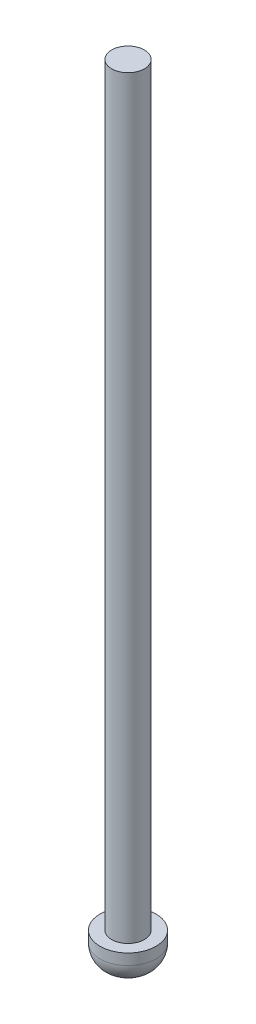
SolidWorks part; units mm, degrees
ref_plane "Alzado" through (0, 0, 0) normal (0, 0, 1) x (1, 0, 0)
ref_plane "Planta" through (0, 0, 0) normal (0, 1, 0) x (1, 0, 0)
ref_plane "Vista lateral" through (0, 0, 0) normal (1, 0, 0) x (0, 0, -1)
sketch "Croquis2" plane through (0, 0, 0) normal (0, 1, 0) x (1, 0, 0)
  circle A0 centre (0, 0) radius 17.25
  dimension "D1" = 34.5
extrude "Saliente-Extruir1" add sketch "Croquis2" along normal blind 794.82
sketch "Croquis4" plane through (0, 0, 0) normal (0, -1, 0) x (1, 0, 0)
  circle A0 centre (0, 0) radius 29.5
  dimension "D1" = 59
extrude "Saliente-Extruir2" add sketch "Croquis4" along normal blind 33.5
sketch3d "Croquis3D2"
  line L0 (0, -33.5, 0) -> (0, 0, 0) construction
  circle A0 centre (0, -33.5, 0) radius 29.5 construction
  point P0 (0, 0, 0)
  point P1 (0, -33.5, 0)
  point P3 (28.5881, -33.5, 7.278)
  point P9 (0, -63, 0)
ref_plane "Plano2" through (0, 0, 0) normal (0.2467, 0, -0.9691) x (-0.9691, 0, -0.2467)
fillet "Redondeo2" radius 22 1 edges at (0, -33.5, -29.5)
